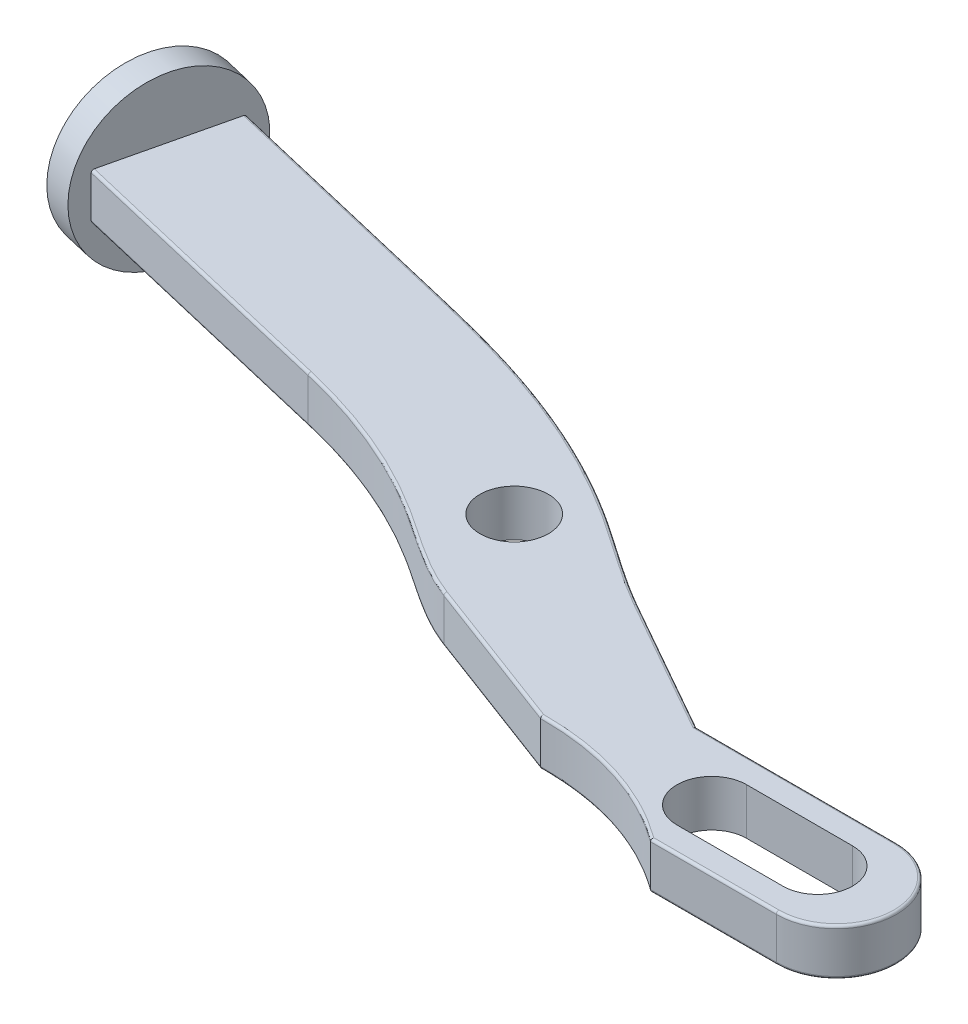
SolidWorks part; units mm, degrees
ref_plane "Спереди XY" through (0, 0, 0) normal (0, 0, 1) x (1, 0, 0)
ref_plane "Сверху XZ" through (0, 0, 0) normal (0, 1, 0) x (1, 0, 0)
ref_plane "Справа ZY" through (0, 0, 0) normal (1, 0, 0) x (0, 0, -1)
sketch "Эскиз1" plane through (0, 0, 0) normal (0, 1, 0) x (1, 0, 0)
  line L0 (0, 0) -> (-9.75, 0)
  line L2 (-22.25, 4) -> (-34.25, 8.5)
  line L11 (-26, 15.2419) -> (-15.5, 9.3)
  line L12 (-15.5, 9.3) -> (0, 9.3)
  line L13 (-54.25, 18) -> (-76.25, 23.2)
  line L16 (-53.9497, 28.2046) -> (-73.9497, 32.9318)
  line L17 (-73.9497, 32.9318) -> (-76.25, 23.2)
  line L21 (-1.45, 4.65) -> (-9.65, 4.65) construction
  line L22 (-1.45, 1.95) -> (-9.65, 1.95)
  line L23 (-1.45, 7.35) -> (-9.65, 7.35)
  arc A3 (0, 9.3) -> (0, 0) centre (0, 4.65) cw
  arc A4 (-1.45, 1.95) -> (-1.45, 7.35) centre (-1.45, 4.65) ccw
  arc A5 (-9.65, 7.35) -> (-9.65, 1.95) centre (-9.65, 4.65) ccw
  circle A7 centre (-36.8, 16.5) radius 2.65
  spline S0 degree 3 poles (-53.9497, 28.2046) (-51.225, 27.5605) (-44.0461, 25.6801) (-34.5435, 21.3222) (-28.506, 16.66) (-26, 15.2419) knots 0 0 0 0 0.269808 0.718748 1 1 1 1
  spline S1 degree 3 poles (-54.25, 18) (-49.2731, 16.8236) (-42.6914, 14.0296) (-36.7521, 9.4383) (-34.25, 8.5) knots 0 0 0 0 0.645146 1 1 1 1
  spline S2 degree 2 poles (-22.25, 4) (-15.2968, 4.03) (-9.75, 0) knots 0 0 0 1 1 1
  point P37 (-5.55, 4.65)
  point P42 (1.25, 4.65)
  point P43 (4.65, 4.65)
  point P44 (-12.35, 4.65)
  dimension "D3" = 13.6
  dimension "D5" = 14.4
  dimension "D13" = 4
  dimension "D17" = 5.2
  dimension "D6" = 12.5
  dimension "D14" = 20
  dimension "D12" = 14.7487
  dimension "D24" = 41.0482
  dimension "D26" = 5.3
  dimension "D1" = 9.3
  dimension "D2" = 3.4
  dimension "D4" = 5.4
  dimension "D7" = 15.5
  dimension "D8" = 12
  dimension "D9" = 22
  dimension "D10" = 10.5
  dimension "D11" = 7.2
  dimension "D15" = 4.5
  dimension "D16" = 9.5
  dimension "D18" = 23.2
  dimension "D19" = 80.9
  dimension "D20" = 33.2907
  dimension "D21" = 21.3
  dimension "D22" = 20
  dimension "D23" = 10
  dimension "D25" = 2.55
  dimension "D27" = 45.8845
  dimension "D28" = 2.7034
  dimension "D29" = 12.4705
  dimension "D30" = 15.2419
  dimension "D31" = 20.0319
  dimension "D32" = 25.9724
extrude "Бобышка-Вытянуть1" add sketch "Эскиз1" along normal mid plane 3.6
sketch "Эскиз4" plane through (-77.409, 0, -18.2967) normal (-0.9732, 0, -0.23) x (-0.23, 0, 0.9732)
  circle A0 centre (-10.0384, 0) radius 6.5
  dimension "D1" = 13
extrude "Бобышка-Вытянуть2" add sketch "Эскиз4" along normal blind 2.2
fillet "Скругление1" radius 0.2 20 edges at (-65.25, -1.8, -20.6) (-65.25, 1.8, -20.6) (-4.875, -1.8, 0) (4.65, -1.8, -4.65) (-4.875, 1.8, 0) (4.65, 1.8, -4.65) (-20.75, -1.8, -12.2709) (-20.75, 1.8, -12.2709) (-28.25, -1.8, -6.25) (-28.25, 1.8, -6.25) (-7.75, -1.8, -9.3) (-7.75, 1.8, -9.3) (-63.9497, -1.8, -30.5682) (-63.9497, 1.8, -30.5682)
